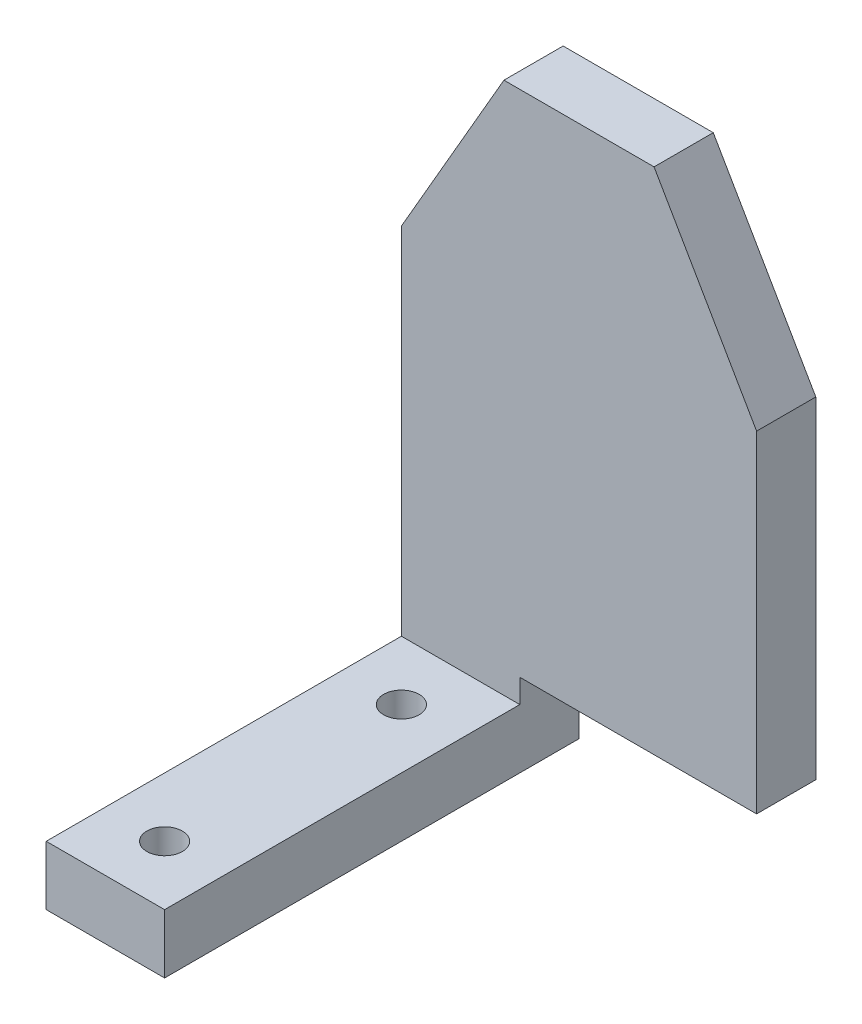
SolidWorks part; units mm, degrees
material "Custom Plastic"
ref_plane "Front Plane" through (0, 0, 0) normal (0, 0, 1) x (1, 0, 0)
ref_plane "Top Plane" through (0, 0, 0) normal (0, 1, 0) x (1, 0, 0)
ref_plane "Right Plane" through (0, 0, 0) normal (1, 0, 0) x (0, 0, -1)
sketch "Sketch1" plane through (0, 0, 0) normal (0, 0, 1) x (1, 0, 0)
  line L0 (0, 35) -> (8.6603, 50)
  line L1 (0, 0) -> (30, 0)
  line L2 (0, 0) -> (0, 35)
  line L3 (8.6603, 50) -> (21.3397, 50)
  line L4 (30, 0) -> (30, 35)
  line L5 (21.3397, 50) -> (30, 35)
  dimension "D1" = 30
  dimension "D2" = 35
  dimension "D3" = 50
  dimension "D4" = 30
  dimension "D5" = 30
extrude "Boss-Extrude1" add sketch "Sketch1" along normal blind 5
sketch "Sketch2" plane through (0, 0, 5) normal (0, 0, 1) x (1, 0, 0)
  line L0 (0, 17.5) -> (30, 17.5) construction
  line L1 (0, 0) -> (10, 0)
  line L2 (0, 0) -> (0, 5)
  line L3 (0, 5) -> (10, 5)
  line L4 (10, 0) -> (10, 5)
  line L5 (0, 35) -> (0, 0) construction
  line L6 (30, 0) -> (30, 35) construction
  dimension "D1" = 10
  dimension "D2" = 5
extrude "Boss-Extrude2" add sketch "Sketch2" along normal blind 30
sketch "Sketch3" plane through (0, 5, 0) normal (0, 1, 0) x (1, 0, 0)
  line L1 (5, -5) -> (5, -35) construction
  line L2 (10, -5) -> (0, -5) construction
  line L3 (10, -35) -> (0, -35) construction
  circle A0 centre (5, -10) radius 1.5
  circle A1 centre (5, -30) radius 1.5
  dimension "D1" = 3
  dimension "D2" = 3
  dimension "D3" = 5
  dimension "D4" = 5
extrude "Cut-Extrude1" cut sketch "Sketch3" against normal up to surface (5 mm away) up to face at (13.3333, 0, 13.3333)
sketch "Sketch4" plane through (0, 0, 5) normal (0, 0, 1) x (1, 0, 0)
  line L0 (30, 0) -> (30, 35) construction
  line L1 (10, 0) -> (30, 0)
  line L2 (10, 0) -> (10, 7)
  line L3 (10, 7) -> (30, 7)
  line L4 (30, 0) -> (30, 7)
  dimension "D1" = 2
extrude "Cut-Extrude2" cut sketch "Sketch4" against normal up to surface (5 mm away) up to face at (15, 28.3333, 0)
